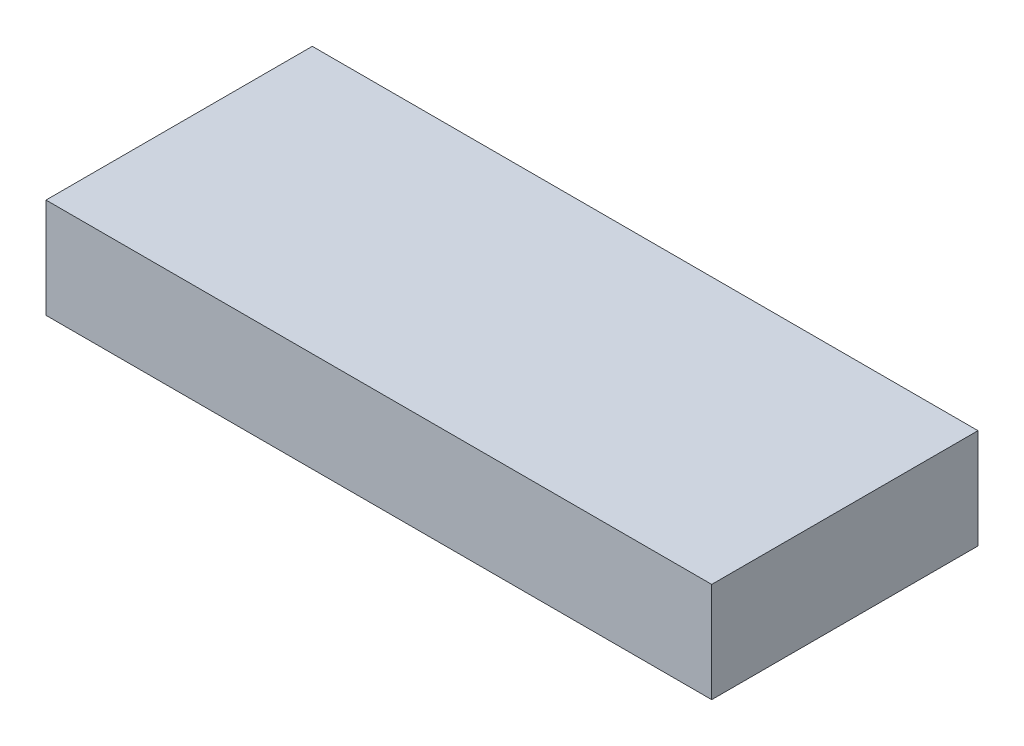
SolidWorks part; units mm, degrees
ref_plane "Front Plane" through (0, 0, 0) normal (0, 0, 1) x (1, 0, 0)
ref_plane "Top Plane" through (0, 0, 0) normal (0, 1, 0) x (1, 0, 0)
ref_plane "Right Plane" through (0, 0, 0) normal (1, 0, 0) x (0, 0, -1)
sketch "Sketch1" plane through (0, 0, 0) normal (0, 1, 0) x (1, 0, 0)
  line L1 (-31.75, 12.7) -> (31.75, 12.7)
  line L2 (-31.75, 12.7) -> (-31.75, -12.7)
  line L3 (-31.75, -12.7) -> (31.75, -12.7)
  line L4 (31.75, 12.7) -> (31.75, -12.7)
  line L5 (-31.75, 12.7) -> (31.75, -12.7) construction
  line L6 (-31.75, -12.7) -> (31.75, 12.7) construction
  point P0 (0, 0)
  dimension "D1" = 63.5
  dimension "D2" = 25.4
extrude "Boss-Extrude1" add sketch "Sketch1" along normal blind 9.525
